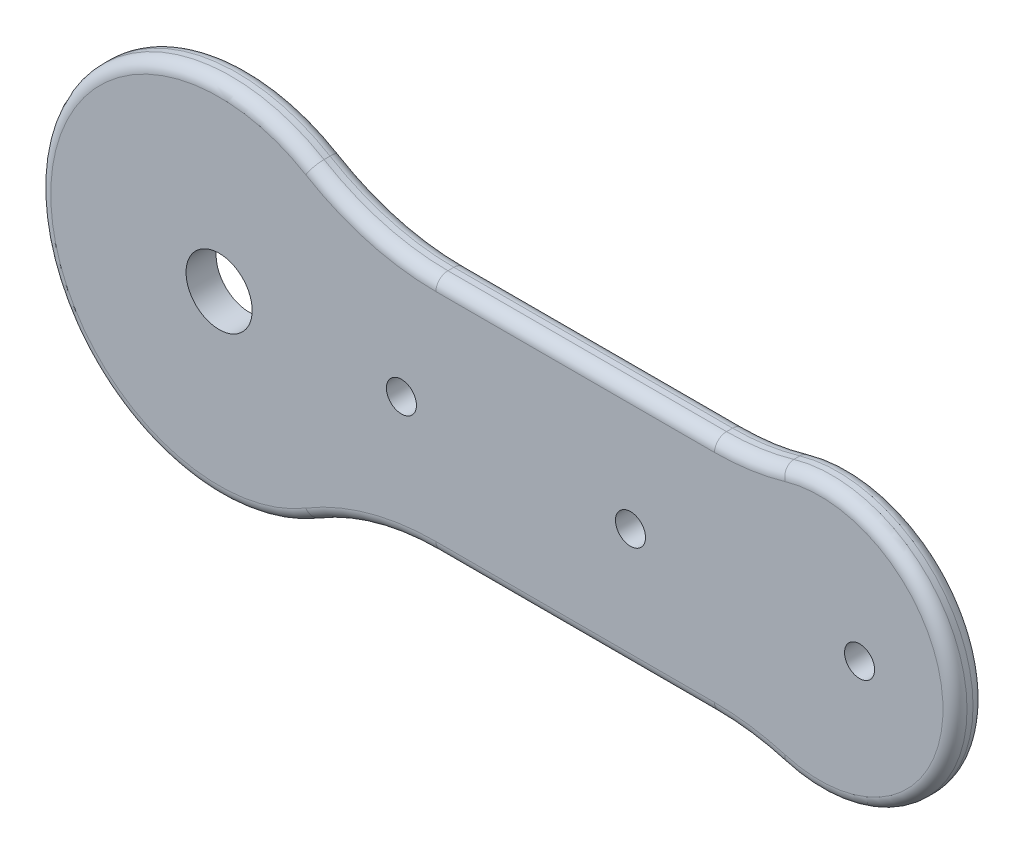
SolidWorks part; units mm, degrees
material "Plain Carbon Steel"
ref_plane "Front Plane" through (0, 0, 0) normal (0, 0, 1) x (1, 0, 0)
ref_plane "Top Plane" through (0, 0, 0) normal (0, 1, 0) x (1, 0, 0)
ref_plane "Right Plane" through (0, 0, 0) normal (1, 0, 0) x (0, 0, -1)
sketch "Sketch1" plane through (0, 0, 0) normal (0, 0, 1) x (1, 0, 0)
  line L1 (-99.9, 40) -> (99.9, 40)
  line L2 (-99.9, 40) -> (-99.9, -40)
  line L3 (-99.9, -40) -> (99.9, -40)
  line L4 (99.9, 40) -> (99.9, -40)
  line L5 (-99.9, 40) -> (99.9, -40) construction
  line L6 (-99.9, -40) -> (99.9, 40) construction
  circle A0 centre (99.9, 0) radius 45
  circle A1 centre (-99.9, 0) radius 60
  circle A2 centre (-99.9, 0) radius 11
  circle A4 centre (36.95, 0) radius 5
  circle A5 centre (-39.25, 0) radius 5
  circle A7 centre (113.15, 0) radius 5
  point P0 (0, 0)
  point P18 (-159.9, 0)
  point P19 (144.9, 0)
  dimension "D2" = 120
  dimension "D3" = 90
  dimension "D5" = 22
  dimension "D6" = 10
  dimension "D7" = 10
  dimension "D8" = 10
  dimension "D10" = 31.75
  dimension "D11" = 76.2
  dimension "D12" = 76.2
  dimension "D1" = 80
  dimension "D4" = 304.8
extrude "Boss-Extrude1" add sketch "Sketch1" along normal blind 10
fillet "Fillet1" radius 80 4 edges at (-55.1786, -40, 5) (-55.1786, 40, 5) (79.2845, -40, 5) (79.2845, 40, 5)
fillet "Fillet2" radius 4 16 edges at (18.5555, 40, 0) (18.5555, 40, 10) (-159.9, 0, 0) (-159.9, 0, 10) (18.5555, -40, 10) (18.5555, -40, 0) (144.9, 0, 10) (144.9, 0, 0) (-49.1699, -42.9101, 10) (-49.1699, -42.9101, 0) (-49.1699, 42.9101, 10) (-49.1699, 42.9101, 0) (76.2137, -40.804, 10) (76.2137, -40.804, 0) (76.2137, 40.804, 10) (76.2137, 40.804, 0)
